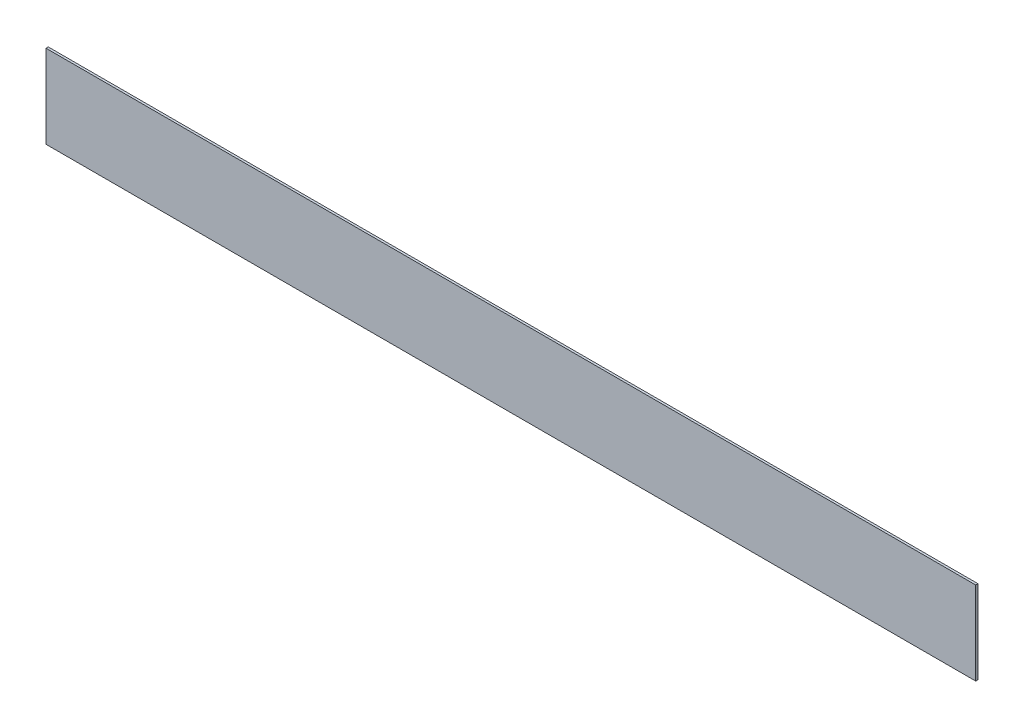
SolidWorks part; units mm, degrees
ref_plane "前视基准面" through (0, 0, 0) normal (0, 0, 1) x (1, 0, 0)
ref_plane "上视基准面" through (0, 0, 0) normal (0, 1, 0) x (1, 0, 0)
ref_plane "右视基准面" through (0, 0, 0) normal (1, 0, 0) x (0, 0, -1)
other "Configuration Table"
sketch "草图1" plane through (0, 0, 0) normal (0, 0, 1) x (1, 0, 0)
  line L1 (0, 0) -> (2056, 0)
  line L2 (0, 0) -> (0, 184)
  line L3 (0, 184) -> (2056, 184)
  line L4 (2056, 0) -> (2056, 184)
  dimension "D1" = 184
  dimension "D2" = 2056
extrude "凸台-拉伸1" add sketch "草图1" along normal blind 5
